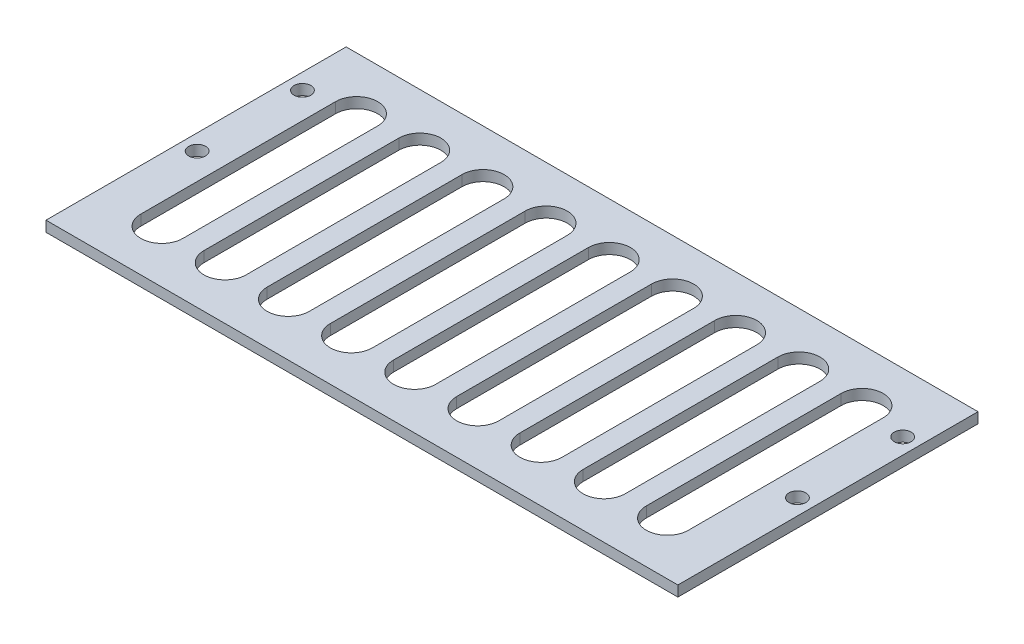
SolidWorks part; units mm, degrees
material "环氧树脂FR-4"
ref_plane "前视基准面" through (0, 0, 0) normal (0, 0, 1) x (1, 0, 0)
ref_plane "上视基准面" through (0, 0, 0) normal (0, 1, 0) x (1, 0, 0)
ref_plane "右视基准面" through (0, 0, 0) normal (1, 0, 0) x (0, 0, -1)
sketch "草图1" plane through (0, 0, 0) normal (0, 1, 0) x (1, 0, 0)
  line L1 (60, -28.5) -> (-60, -28.5)
  line L2 (60, -28.5) -> (60, 28.5)
  line L3 (60, 28.5) -> (-60, 28.5)
  line L4 (-60, -28.5) -> (-60, 28.5)
  line L5 (60, -28.5) -> (-60, 28.5) construction
  line L6 (60, 28.5) -> (-60, -28.5) construction
  point P0 (0, 0)
  dimension "D1" = 120
  dimension "D2" = 57
extrude "凸台-拉伸1" add sketch "草图1" along normal blind 2
sketch "草图2" plane through (0, 2, 0) normal (0, 1, 0) x (1, 0, 0)
  line L0 (-57, 17.2) -> (-57, -2.8) construction
  line L1 (0, 0) -> (0, 28.5) construction
  line L2 (60, 28.5) -> (-60, 28.5) construction
  line L3 (-60, 28.5) -> (-60, -28.5) construction
  line L4 (-60, -28.5) -> (60, -28.5) construction
  circle A0 centre (-57, 17.2) radius 1.6
  circle A1 centre (-57, -2.8) radius 1.6
  circle A2 centre (57, -2.8) radius 1.6
  circle A3 centre (57, 17.2) radius 1.6
  dimension "D2" = 3.2
  dimension "D4" = 25.7
  dimension "D1" = 20
  dimension "D3" = 3
extrude "切除-拉伸1" cut sketch "草图2" against normal through all
sketch "草图3" plane through (0, 2, 0) normal (0, 1, 0) x (1, 0, 0)
  line L1 (4, -18.5) -> (-4, -18.5)
  line L2 (4, -18.5) -> (4, 18.5)
  line L3 (4, 18.5) -> (-4, 18.5)
  line L4 (-4, -18.5) -> (-4, 18.5)
  line L5 (4, -18.5) -> (-4, 18.5) construction
  line L6 (4, 18.5) -> (-4, -18.5) construction
  circle A0 centre (0, 18.5) radius 4
  circle A1 centre (0, -18.5) radius 4
  point P0 (0, 0)
  dimension "D2" = 8
  dimension "D1" = 37
extrude "切除-拉伸2" cut sketch "草图3" against normal through all contours A1 L2 A0 L4 | L3 A0 | L3 A0 | L1 A1 | L1 A1
pattern_linear "阵列(线性)1" count 5 spacing 12 along (1, 0, 0) count 5 spacing 12 along (-1, 0, 0) of "切除-拉伸2"
